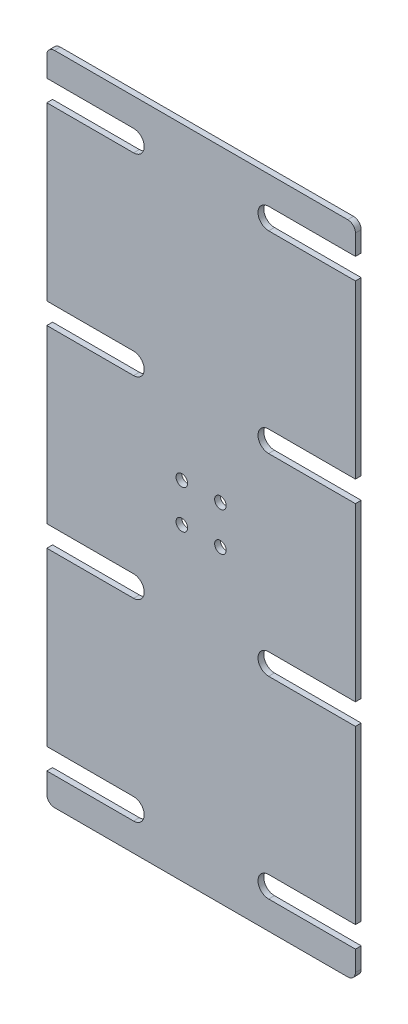
SolidWorks part; units mm, degrees
ref_plane "前视基准面" through (0, 0, 0) normal (0, 0, 1) x (1, 0, 0)
ref_plane "上视基准面" through (0, 0, 0) normal (0, 1, 0) x (1, 0, 0)
ref_plane "右视基准面" through (0, 0, 0) normal (1, 0, 0) x (0, 0, -1)
sketch "草图1" plane through (0, 0, 0) normal (0, 0, 1) x (1, 0, 0)
  line L0 (80, 90) -> (100, 90)
  line L1 (0, 0) -> (80, 0)
  line L2 (0, 0) -> (0, 70)
  line L3 (0, 160) -> (80, 160)
  line L4 (80, 0) -> (80, 70)
  line L5 (100, 90) -> (100, 70)
  line L6 (100, 70) -> (80, 70)
  line L7 (0, 70) -> (-20, 70)
  line L8 (-20, 70) -> (-20, 90)
  line L9 (-20, 90) -> (0, 90)
  line L10 (0, 90) -> (0, 160)
  line L11 (80, 90) -> (80, 160)
  dimension "D1" = 160
  dimension "D2" = 80
  dimension "D3" = 20
  dimension "D4" = 20
  dimension "D5" = 20
  dimension "D6" = 20
  dimension "D7" = 70
extrude "凸台-拉伸1" add sketch "草图1" along normal blind 1.5
sketch "草图2" plane through (0, 0, 1.5) normal (0, 0, 1) x (1, 0, 0)
  line L0 (0, 0) -> (80, 0) construction
  line L1 (0, 70) -> (0, 0) construction
  line L2 (57.5, 152.25) -> (80, 152.25)
  line L4 (80, 90) -> (80, 160) construction
  line L5 (57.5, 157.75) -> (80, 157.75)
  line L6 (22.5, 152.25) -> (0, 152.25)
  line L7 (0, 160) -> (0, 90) construction
  line L8 (22.5, 157.75) -> (0, 157.75)
  line L9 (57.5, 102.25) -> (80, 102.25)
  line L10 (57.5, 107.75) -> (80, 107.75)
  line L11 (22.5, 107.75) -> (0, 107.75)
  line L12 (22.5, 102.25) -> (0, 102.25)
  line L13 (22.5, 57.75) -> (0, 57.75)
  line L14 (22.5, 52.25) -> (0, 52.25)
  line L15 (57.5, 52.25) -> (80, 52.25)
  line L16 (80, 0) -> (80, 70) construction
  line L17 (57.5, 57.75) -> (80, 57.75)
  line L18 (22.5, 7.75) -> (0, 7.75)
  line L19 (22.5, 2.25) -> (0, 2.25)
  line L20 (57.5, 7.75) -> (80, 7.75)
  line L21 (57.5, 2.25) -> (80, 2.25)
  line L22 (80, 157.75) -> (80, 152.25)
  line L23 (0, 157.75) -> (0, 152.25)
  line L24 (0, 107.75) -> (0, 102.25)
  line L25 (80, 107.75) -> (80, 102.25)
  line L26 (80, 57.75) -> (80, 52.25)
  line L27 (0, 57.75) -> (0, 52.25)
  line L28 (0, 7.75) -> (0, 2.25)
  line L29 (80, 7.75) -> (80, 2.25)
  arc A0 (57.5, 7.75) -> (57.5, 2.25) centre (57.5, 5) ccw
  arc A1 (57.5, 57.75) -> (57.5, 52.25) centre (57.5, 55) ccw
  arc A2 (57.5, 107.75) -> (57.5, 102.25) centre (57.5, 105) ccw
  arc A3 (57.5, 157.75) -> (57.5, 152.25) centre (57.5, 155) ccw
  arc A4 (22.5, 152.25) -> (22.5, 157.75) centre (22.5, 155) ccw
  arc A5 (22.5, 102.25) -> (22.5, 107.75) centre (22.5, 105) ccw
  arc A6 (22.5, 52.25) -> (22.5, 57.75) centre (22.5, 55) ccw
  arc A7 (22.5, 2.25) -> (22.5, 7.75) centre (22.5, 5) ccw
  dimension "D1" = 5.5
  dimension "D2" = 5.5
  dimension "D3" = 5.5
  dimension "D4" = 5.5
  dimension "D5" = 50
  dimension "D6" = 50
  dimension "D7" = 50
  dimension "D8" = 5
  dimension "D9" = 2
  dimension "D10" = 22.5
extrude "切除-拉伸1" cut sketch "草图2" against normal blind 1.5
sketch "草图3" plane through (0, 0, 1.5) normal (0, 0, 1) x (1, 0, 0)
  line L0 (0, 90) -> (-20, 90) construction
  line L2 (-20, 90) -> (-20, 70) construction
  line L3 (100, 70) -> (100, 90) construction
  line L4 (100, 90) -> (80, 90) construction
  circle A0 centre (90, 80) radius 2
  circle A1 centre (-10, 80) radius 2
  point P10 (100, 80)
  dimension "D1" = 4
  dimension "D2" = 4
  dimension "D4" = 10
  dimension "D5" = 10
  dimension "D6" = 10
  dimension "D3" = 10
extrude "切除-拉伸2" cut sketch "草图3" against normal blind 1.5
sketch "草图4" plane through (0, 0, 0) normal (0, 0, -1) x (-1, 0, 0)
  line L1 (0, 160) -> (-80, 160)
  line L2 (0, 160) -> (0, 165)
  line L3 (0, 165) -> (-80, 165)
  line L4 (-80, 160) -> (-80, 165)
  line L5 (0, 0) -> (-80, 0)
  line L6 (0, 0) -> (0, -5)
  line L7 (0, -5) -> (-80, -5)
  line L8 (-80, 0) -> (-80, -5)
  dimension "D1" = 5
  dimension "D2" = 5
extrude "凸台-拉伸2" add sketch "草图4" against normal blind 1.5
fillet "圆角1" radius 2 4 edges at (80, 165, 0.75) (0, 165, 0.75) (0, -5, 0.75) (80, -5, 0.75)
sketch "草图5" plane through (0, 0, 1.5) normal (0, 0, 1) x (1, 0, 0)
  line L0 (78, -5) -> (2, -5) construction
  line L1 (0, 165) -> (80, 165)
  line L2 (0, 165) -> (0, -5)
  line L3 (0, -5) -> (80, -5)
  line L4 (80, 165) -> (80, -5)
  line L5 (80, 7.75) -> (80, 52.25) construction
  line L6 (2, 165) -> (78, 165) construction
  line L7 (0, 152.25) -> (0, 107.75) construction
extrude "切除-拉伸3" cut sketch "草图5" against normal through all flip side to cut
sketch "草图6" plane through (0, 0, 0) normal (0, 0, -1) x (-1, 0, 0)
  line L0 (-80, 80) -> (26.8416, 80) construction
  line L1 (-80, 57.75) -> (-80, 102.25) construction
  line L2 (-40, -5) -> (-40, 194.401) construction
  line L3 (-78, -5) -> (-2, -5) construction
  circle A0 centre (-35, 85) radius 1.5
  circle A1 centre (-35, 75) radius 1.5
  circle A2 centre (-45, 75) radius 1.5
  circle A3 centre (-45, 85) radius 1.5
  dimension "D1" = 3
  dimension "D2" = 5
  dimension "D3" = 5
extrude "切除-拉伸4" cut sketch "草图6" against normal through all
